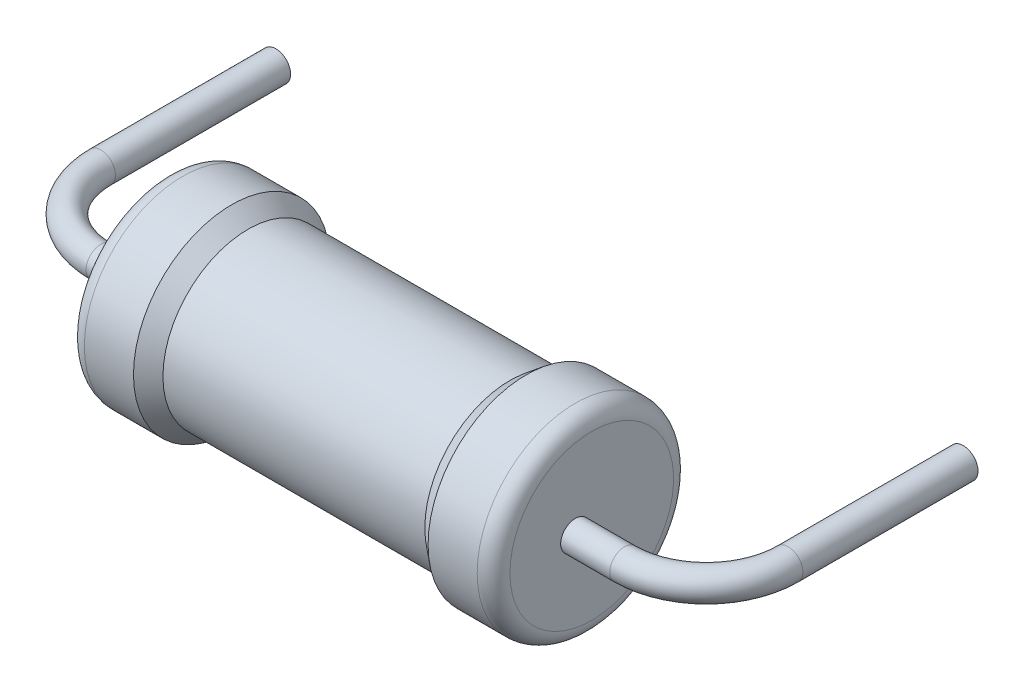
SolidWorks part; units mm, degrees
ref_plane "Спереди" through (0, 0, 0) normal (0, 0, 1) x (1, 0, 0)
ref_plane "Сверху" through (0, 0, 0) normal (0, 1, 0) x (1, 0, 0)
ref_plane "Справа" through (0, 0, 0) normal (1, 0, 0) x (0, 0, -1)
sketch "Эскиз1" plane through (0, 0, 0) normal (0, 0, 1) x (1, 0, 0)
  line L0 (7.5, 0) -> (7.5, 2.2883) construction
  circle A0 centre (0, 0) radius 0.45
ref_plane "Плоскость1" through (0, 0, 3.35) normal (0, 0, 1) x (1, 0, 0)
sketch "Эскиз2" plane through (0, 0, 3.35) normal (0, 0, 1) x (1, 0, 0)
  line L0 (0, 0) -> (17, 0) construction
  line L1 (10.5, 0) -> (10.5, 5.2095) construction
  line L2 (4, 0) -> (17, 0)
  line L3 (4, 0) -> (4, 3)
  line L4 (4, 3) -> (6, 3)
  line L5 (15, 3) -> (14.5, 2.6)
  line L7 (6, 3) -> (6.5, 2.6)
  line L8 (6.5, 2.6) -> (14.5, 2.6)
  line L9 (17, 3) -> (15, 3)
  line L10 (17, 0) -> (17, 3)
  point P13 (10.5, 2.6)
  dimension "D1" = 4
  dimension "D2" = 2
  dimension "D3" = 13
  dimension "D4" = 3
  dimension "D5" = 2.6
  dimension "D6" = 4
revolve "Повернуть1" add sketch "Эскиз2" angle 360 about L0
sketch "Эскиз3" plane through (0, 0, 0) normal (0, 1, 0) x (1, 0, 0)
  line L0 (4, -0.35) -> (4, -6.35) construction
  line L1 (2.5, -3.35) -> (18.5, -3.35)
  line L2 (10.5, 1.713) -> (10.5, -6.8065) construction
  line L3 (20.5, 0) -> (20.5, -1.35)
  line L4 (17, -6.35) -> (17, -0.35) construction
  line L5 (0.5, -1.35) -> (0.5, 0)
  arc A0 (0.5, -1.35) -> (2.5, -3.35) centre (2.5, -1.35) ccw
  arc A1 (20.5, -1.35) -> (18.5, -3.35) centre (18.5, -1.35) cw
  point P10 (10.5, -3.35)
  dimension "D1" = 16
  dimension "D2" = 2
sweep "По траектории1" add profiles "Эскиз1" path "Эскиз3"
fillet "Скругление1" radius 0.5 2 edges at (4, 0, 6.35) (17, 0, 6.35)
sketch "Эскиз4" plane through (0, 0, 0) normal (0, 0, -1) x (-1, 0, 0)
  circle A0 centre (0, 0) radius 0.45
  circle A1 centre (-21, 0) radius 0.45
  circle A3 centre (-21, 0) radius 0.45 construction
extrude "Вытянуть1" add sketch "Эскиз4" along normal blind 4
